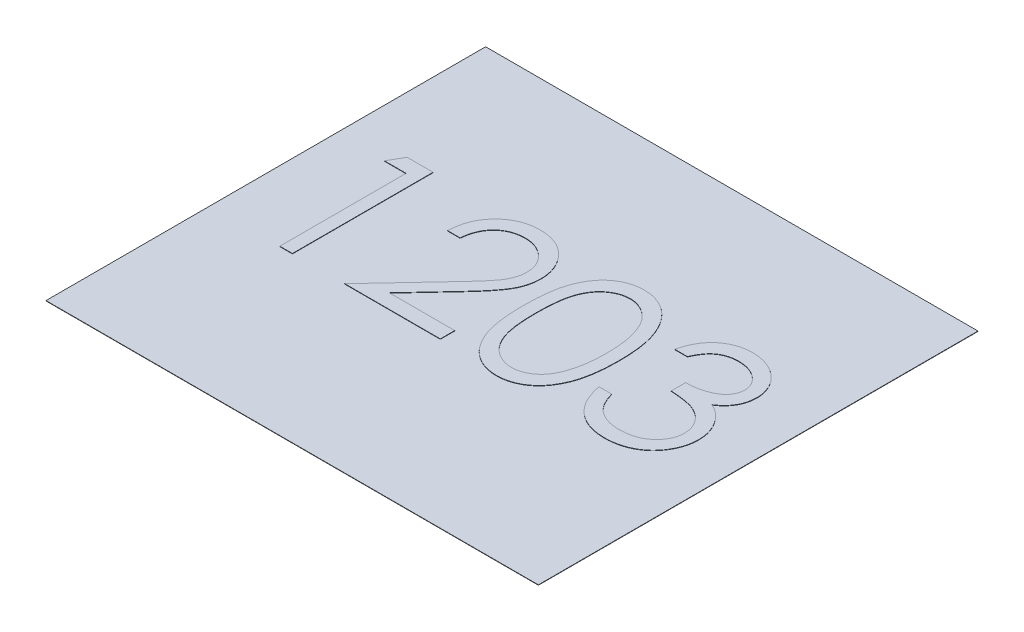
SolidWorks part; units mm, degrees
ref_plane "Plano frontal" through (0, 0, 0) normal (0, 0, 1) x (1, 0, 0)
ref_plane "Plano superior" through (0, 0, 0) normal (0, 1, 0) x (1, 0, 0)
ref_plane "Plano direito" through (0, 0, 0) normal (1, 0, 0) x (0, 0, -1)
sketch "Esboço1" plane through (0, 0, 0) normal (0, 1, 0) x (1, 0, 0)
  line L1 (-1.4, 1.25) -> (0, 1.25)
  line L2 (-1.4, 1.25) -> (-1.4, 0)
  line L3 (-1.4, 0) -> (0, 0)
  line L4 (0, 1.25) -> (0, 0)
  dimension "D1" = 1.4
  dimension "D2" = 1.25
extrude "Ressalto-extrusão1" add sketch "Esboço1" along normal blind 0.001
sketch "Esboço2" plane through (0, 0.001, 0) normal (0, 1, 0) x (1, 0, 0)
  text T0 "1203" font "Century Gothic" height 0.4
extrude "Ressalto-extrusão2" add sketch "Esboço2" along normal blind 0.001
